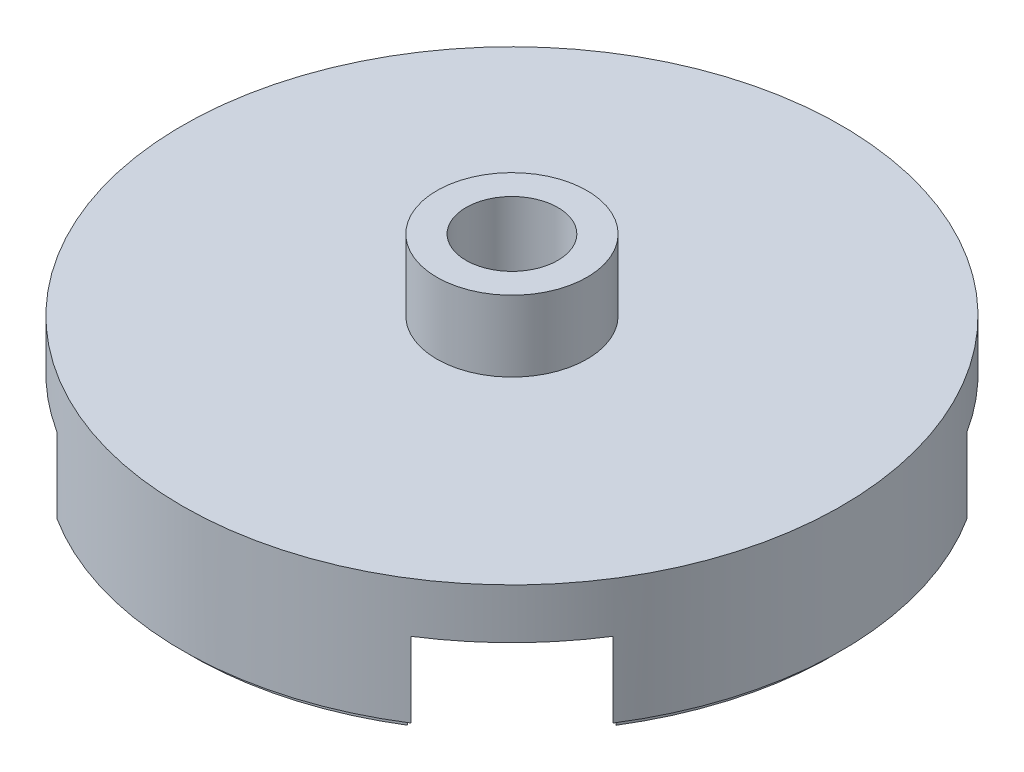
SolidWorks part; units mm, degrees
material "ABS"
ref_plane "Front Plane" through (0, 0, 0) normal (0, 0, 1) x (1, 0, 0)
ref_plane "Top Plane" through (0, 0, 0) normal (0, 1, 0) x (1, 0, 0)
ref_plane "Right Plane" through (0, 0, 0) normal (1, 0, 0) x (0, 0, -1)
sketch "Sketch1" plane through (0, 0, 0) normal (0, 1, 0) x (1, 0, 0)
  circle A0 centre (0, 0) radius 7.9
  dimension "D1" = 15.8
extrude "Boss-Extrude1" add sketch "Sketch1" along normal blind 1.2
sketch "Sketch2" plane through (0, 1.2, 0) normal (0, 1, 0) x (1, 0, 0)
  circle A0 centre (0, 0) radius 1.8
  dimension "D1" = 3.6
extrude "Boss-Extrude2" add sketch "Sketch2" along normal blind 1.7
sketch "Sketch3" plane through (0, 2.9, 0) normal (0, 1, 0) x (1, 0, 0)
  circle A0 centre (0, 0) radius 1.1
  circle A1 centre (0, 0) radius 1.8 construction
  dimension "D1" = 0.7
extrude "Cut-Extrude1" cut sketch "Sketch3" against normal through all both and the other way through all
sketch "Sketch4" plane through (0, 0, 0) normal (0, -1, 0) x (1, 0, 0)
  line L0 (4.2447, -6.6628) -> (2.951, -5.9035)
  line L1 (-4.2447, -6.6628) -> (-2.951, -5.9035)
  arc A0 (4.2447, -6.6628) -> (-4.2447, -6.6628) centre (0, 0) cw
  circle A1 centre (0, 0) radius 7.9 construction
  arc A2 (2.951, -5.9035) -> (-2.951, -5.9035) centre (0, 0) cw
  point P8 (0, -6.6)
  point P9 (0, -7.9)
  dimension "D2" = 1.5
  dimension "D3" = 65
  dimension "D1" = 1.3
extrude "Boss-Extrude3" add sketch "Sketch4" along normal blind 2
sketch "Sketch5" plane through (0, -2, 0) normal (0, -1, 0) x (1, 0, 0)
  line L0 (4.2447, -6.6628) -> (2.951, -5.9035) construction
  line L1 (-2.951, -5.9035) -> (-4.2447, -6.6628) construction
  line L2 (4.2447, -6.6628) -> (2.951, -5.9035)
  line L3 (-2.951, -5.9035) -> (-4.2447, -6.6628)
  line L6 (-4.0503, -6.5487) -> (-4.2447, -6.6628)
  line L7 (4.2447, -6.6628) -> (4.0503, -6.5487)
  arc A0 (4.0503, -6.5487) -> (-4.0503, -6.5487) centre (0, 0) cw
  arc A2 (-4.2447, -6.6628) -> (4.2447, -6.6628) centre (0, 0) ccw
  arc A3 (-2.951, -5.9035) -> (2.951, -5.9035) centre (0, 0) ccw
  arc A4 (-4.2447, -6.6628) -> (4.2447, -6.6628) centre (0, 0) ccw
  point P14 (0, -7.9)
  point P15 (0, -7.7)
  dimension "D2" = 0.2
  dimension "D1" = 0
extrude "Cut-Extrude2" cut sketch "Sketch5" against normal blind 0.2
pattern_circular "CirPattern1" count 4 over 360 about axis through (0, 0, 0) along (0, 1, 0) of "Boss-Extrude3", "Cut-Extrude2"
sketch "Sketch6" plane through (0, 0, 0) normal (0, -1, 0) x (1, 0, 0)
  circle A0 centre (0, 0) radius 1.7
  circle A1 centre (0, 0) radius 1.1 construction
  circle A2 centre (0, 0) radius 1.1
  dimension "D1" = 0.6
extrude "Boss-Extrude4" add sketch "Sketch6" along normal blind 2
